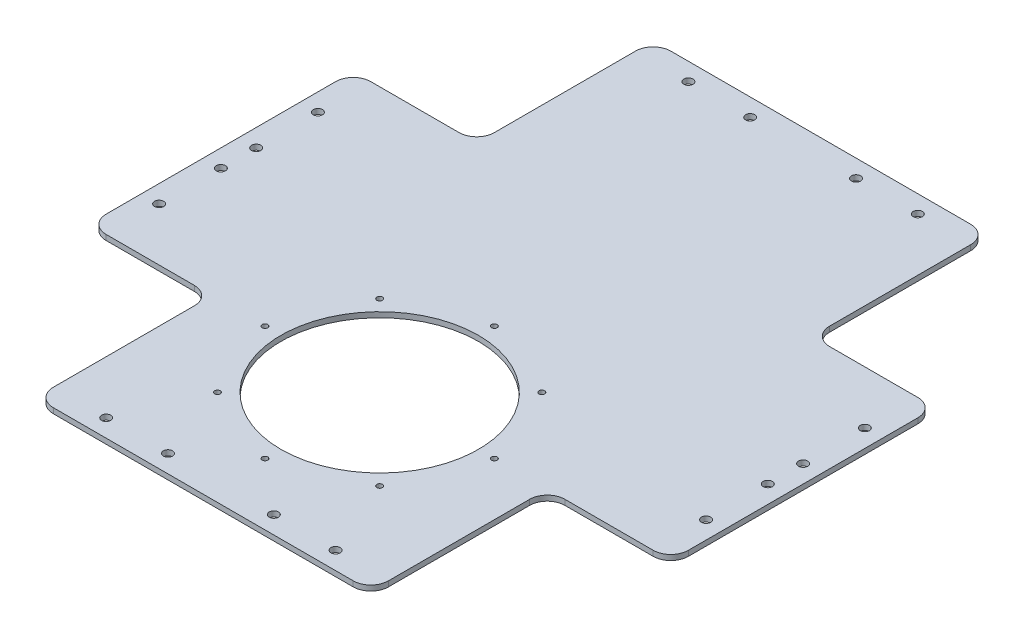
SolidWorks part; units mm, degrees
ref_plane "Front Plane" through (0, 0, 0) normal (0, 0, 1) x (1, 0, 0)
ref_plane "Top Plane" through (0, 0, 0) normal (0, 1, 0) x (1, 0, 0)
ref_plane "Right Plane" through (0, 0, 0) normal (1, 0, 0) x (0, 0, -1)
sketch "Sketch1" plane through (0, 0, 0) normal (0, 1, 0) x (1, 0, 0)
  line L0 (0, 100) -> (330, 100) construction
  line L1 (0, 0) -> (330, 0) construction
  line L2 (0, 0) -> (0, 350) construction
  line L3 (0, 350) -> (330, 350) construction
  line L4 (330, 0) -> (330, 350) construction
  line L5 (0, 0) -> (330, 0)
  line L6 (0, 0) -> (0, 250)
  line L7 (0, 250) -> (330, 250)
  line L8 (330, 0) -> (330, 250)
  line L9 (70, 250) -> (260, 250)
  line L10 (70, 250) -> (70, 350)
  line L11 (70, 350) -> (260, 350)
  line L12 (260, 250) -> (260, 350)
  line L14 (0, 0) -> (70, 0)
  line L15 (0, 0) -> (0, 100)
  line L16 (0, 100) -> (70, 100)
  line L17 (70, 0) -> (70, 100)
  line L18 (330, 0) -> (260, 0)
  line L19 (330, 0) -> (330, 100)
  line L20 (330, 100) -> (260, 100)
  line L21 (260, 0) -> (260, 100)
  circle A0 centre (165, 100) radius 56
  point P11 (165, 350)
  point P12 (165, 350)
  dimension "D5" = 112
  dimension "D1" = 330
  dimension "D2" = 350
  dimension "D3" = 100
  dimension "D4" = 70
  dimension "D6" = 100
  dimension "D7" = 100
extrude "Boss-Extrude1" add sketch "Sketch1" along normal blind 3 contours L5 L8 L7 L6 A0 | L7 L12 L11 L10
fillet "Fillet1" radius 10 12 edges at (70, 1.5, 0) (70, 1.5, -100) (0, 1.5, -100) (0, 1.5, -250) (70, 1.5, -250) (70, 1.5, -350) (260, 1.5, -350) (260, 1.5, -250) (330, 1.5, -250) (330, 1.5, -100) (260, 1.5, -100) (260, 1.5, 0)
sketch "Sketch2" plane through (0, 3, 0) normal (0, 1, 0) x (1, 0, 0)
  line L0 (80, 350) -> (250, 350) construction
  line L1 (0, 0) -> (330, 0) construction
  line L2 (0, 0) -> (0, 350) construction
  line L3 (0, 350) -> (330, 350) construction
  line L4 (330, 0) -> (330, 350) construction
  line L5 (330, 110) -> (330, 240) construction
  line L6 (10, 10) -> (10, 340) construction
  line L7 (10, 340) -> (320, 340) construction
  line L8 (320, 10) -> (320, 340) construction
  line L9 (10, 10) -> (320, 10) construction
  line L10 (70, 260) -> (70, 340) construction
  line L11 (260, 260) -> (260, 340) construction
  line L12 (270, 250) -> (320, 250) construction
  line L13 (260, 10) -> (260, 90) construction
  line L14 (70, 10) -> (70, 90) construction
  line L15 (320, 100) -> (270, 100) construction
  line L16 (10, 100) -> (60, 100) construction
  line L17 (10, 250) -> (60, 250) construction
  circle A0 centre (100, 340) radius 2.6
  circle A1 centre (135, 340) radius 2.6
  circle A2 centre (195, 340) radius 2.6
  circle A3 centre (230, 340) radius 2.6
  circle A4 centre (10, 220) radius 2.6
  circle A5 centre (10, 185) radius 2.6
  circle A6 centre (10, 130) radius 2.6
  circle A7 centre (10, 165) radius 2.6
  circle A8 centre (100, 10) radius 2.6
  circle A9 centre (135, 10) radius 2.6
  circle A10 centre (195, 10) radius 2.6
  circle A11 centre (230, 10) radius 2.6
  circle A12 centre (320, 130) radius 2.6
  circle A13 centre (320, 165) radius 2.6
  circle A14 centre (320, 220) radius 2.6
  circle A15 centre (320, 185) radius 2.6
  circle A16 centre (165, 100) radius 65 construction
  circle A18 centre (165, 165) radius 1.6
  circle A19 centre (210.9619, 145.9619) radius 1.6
  circle A20 centre (230, 100) radius 1.6
  circle A21 centre (210.9619, 54.0381) radius 1.6
  circle A22 centre (165, 35) radius 1.6
  circle A23 centre (119.0381, 54.0381) radius 1.6
  circle A24 centre (100, 100) radius 1.6
  circle A25 centre (119.0381, 145.9619) radius 1.6
  point P84 (165, 100)
  dimension "D2" = 5.2
  dimension "D4" = 35
  dimension "D5" = 35
  dimension "D7" = 30
  dimension "D8" = 35
  dimension "D10" = 35
  dimension "D12" = 35
  dimension "D14" = 35
  dimension "D16" = 35
  dimension "D17" = 30
  dimension "D18" = 35
  dimension "D19" = 130
  dimension "D20" = 3.2
  dimension "D3" = 30
  dimension "D6" = 30
  dimension "D9" = 30
  dimension "D11" = 30
  dimension "D13" = 30
  dimension "D15" = 30
  dimension "D1" = 10
  dimension "D21" = 8
extrude "Cut-Extrude1" cut sketch "Sketch2" against normal through all
sketch "Sketch3" plane through (0, 3, 0) normal (0, 1, 0) x (1, 0, 0)
  circle A0 centre (165, 100) radius 56
  circle A1 centre (165, 100) radius 47.5
  circle A2 centre (165, 100) radius 56 construction
  dimension "D1" = 95
extrude "Boss-Extrude2" [suppressed] add sketch "Sketch3" against normal up to surface (3 mm away)
